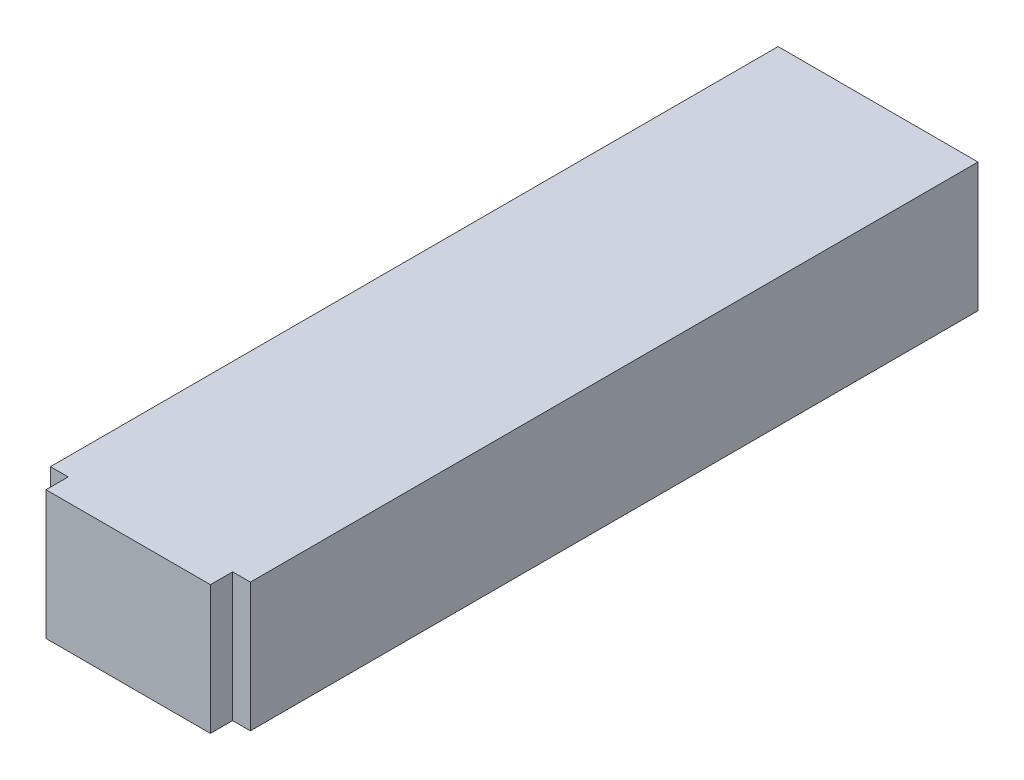
SolidWorks part; units mm, degrees
material "AISI 1020"
ref_plane "Спереди" through (0, 0, 0) normal (0, 0, 1) x (1, 0, 0)
ref_plane "Сверху" through (0, 0, 0) normal (0, 1, 0) x (1, 0, 0)
ref_plane "Справа" through (0, 0, 0) normal (1, 0, 0) x (0, 0, -1)
sketch "Эскиз1" plane through (0, 0, 0) normal (0, 1, 0) x (1, 0, 0)
  line L0 (-740, -6150) -> (-740, -6350)
  line L1 (-900, 400) -> (900, 400)
  line L2 (-900, 400) -> (-900, -6150)
  line L3 (-900, -6150) -> (-740, -6150)
  line L4 (900, 400) -> (900, -6150)
  line L5 (-740, -6350) -> (740, -6350)
  line L6 (740, -6350) -> (740, -6150)
  line L7 (740, -6150) -> (900, -6150)
extrude "Бобышка-Вытянуть1" add sketch "Эскиз1" against normal up to surface (1160 mm away)
